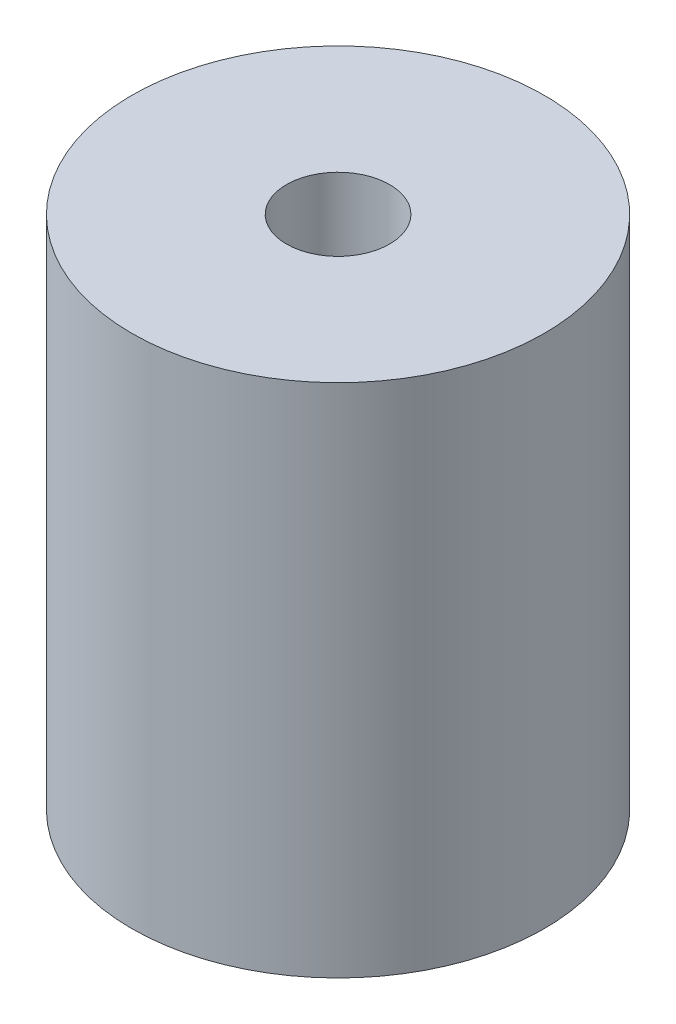
SolidWorks part; units mm, degrees
ref_plane "前视基准面" through (0, 0, 0) normal (0, 0, 1) x (1, 0, 0)
ref_plane "上视基准面" through (0, 0, 0) normal (0, 1, 0) x (1, 0, 0)
ref_plane "右视基准面" through (0, 0, 0) normal (1, 0, 0) x (0, 0, -1)
other "Configuration Table"
sketch "草图1" plane through (0, 0, 0) normal (0, 1, 0) x (1, 0, 0)
  circle A0 centre (0, 0) radius 10
  dimension "D1" = 20
extrude "凸台-拉伸1" add sketch "草图1" along normal blind 25
hole_wizard "孔1" positions "草图2" profile "草图3" legacy
sketch "草图2" plane through (0, 25, 0) normal (0, 1, 0) x (1, 0, 0)
  point P0 (0, 0)
sketch "草图3" plane through (0, 25, 0) normal (1, 0, 0) x (0, 0, 1)
  line L0 (0, 0) -> (0, 12.5)
  line L1 (0, 12.5) -> (2.5, 12.5)
  line L2 (2.5, 12.5) -> (2.5, 0)
  line L3 (2.5, 0) -> (0, 0)
  line L4 (0, 110) -> (0, -10) construction
  dimension "直径" = 5
  dimension "深度" = 12.5
hole_wizard "孔2" positions "草图4" profile "草图5" legacy
sketch "草图4" plane through (0, 0, 0) normal (0, -1, 0) x (-1, 0, 0)
  point P0 (0, 0)
sketch "草图5" plane through (0, 0, 0) normal (1, 0, 0) x (0, 0, -1)
  line L0 (0, 0) -> (0, 12.5)
  line L1 (0, 12.5) -> (4, 12.5)
  line L2 (4, 12.5) -> (4, 0)
  line L3 (4, 0) -> (0, 0)
  line L4 (0, 110) -> (0, -10) construction
  dimension "直径" = 8
  dimension "深度" = 12.5
